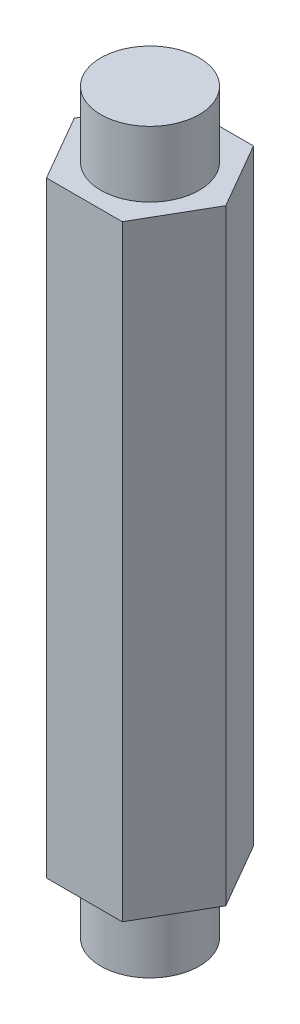
SolidWorks part; units mm, degrees
ref_plane "Alzado" through (0, 0, 0) normal (0, 0, 1) x (1, 0, 0)
ref_plane "Planta" through (0, 0, 0) normal (0, 1, 0) x (1, 0, 0)
ref_plane "Vista lateral" through (0, 0, 0) normal (1, 0, 0) x (0, 0, -1)
sketch "Croquis1" plane through (0, 0, 0) normal (0, 1, 0) x (1, 0, 0)
  line L1 (7.3323, 0) -> (3.6662, 6.35)
  line L2 (3.6662, 6.35) -> (-3.6662, 6.35)
  line L3 (-3.6662, 6.35) -> (-7.3323, 0)
  line L4 (-7.3323, 0) -> (-3.6662, -6.35)
  line L5 (-3.6662, -6.35) -> (3.6662, -6.35)
  line L6 (3.6662, -6.35) -> (7.3323, 0)
  circle A0 centre (0, 0) radius 6.35 construction
  dimension "D1" = 12.7
extrude "Saliente-Extruir1" add sketch "Croquis1" along normal blind 58.68
sketch "Croquis2" plane through (0, 58.68, 0) normal (0, 1, 0) x (1, 0, 0)
  circle A0 centre (0, 0) radius 4.7625
  dimension "D1" = 9.525
extrude "Saliente-Extruir2" add sketch "Croquis2" along normal blind 6.35
sketch "Croquis3" plane through (0, 0, 0) normal (0, -1, 0) x (1, 0, 0)
  circle A0 centre (0, 0) radius 4.7625
  dimension "D1" = 9.525
extrude "Saliente-Extruir3" add sketch "Croquis3" along normal blind 6.35
